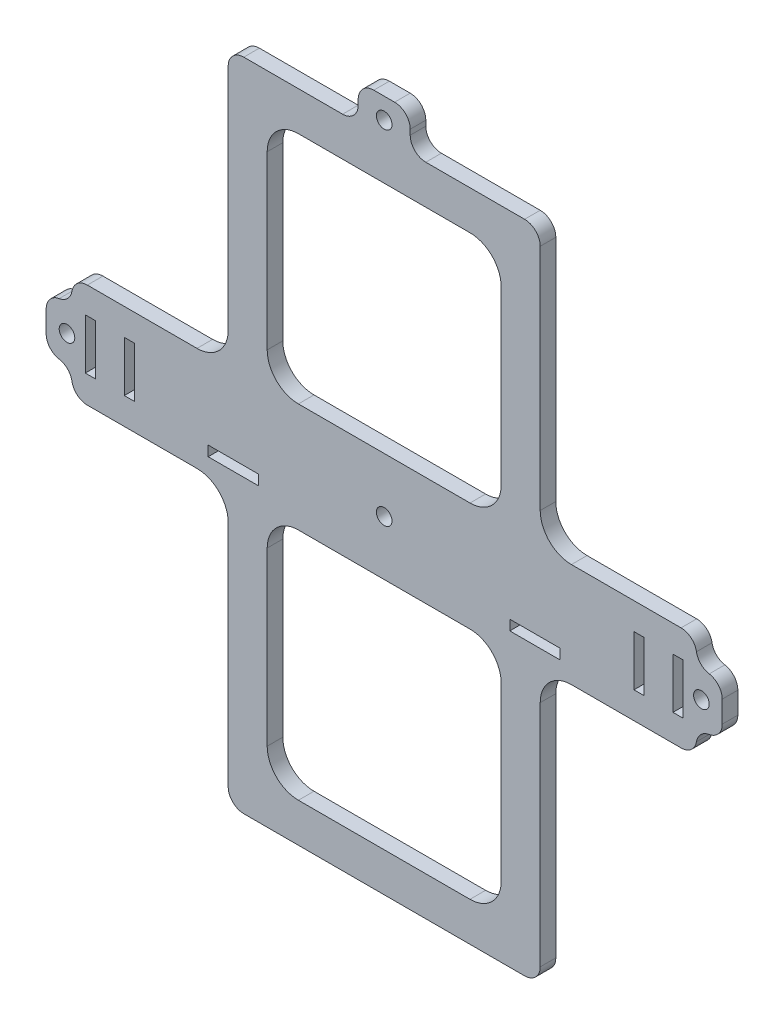
SolidWorks part; units mm, degrees
ref_plane "Спереди" through (0, 0, 0) normal (0, 0, 1) x (1, 0, 0)
ref_plane "Сверху" through (0, 0, 0) normal (0, 1, 0) x (1, 0, 0)
ref_plane "Справа" through (0, 0, 0) normal (1, 0, 0) x (0, 0, -1)
sketch "Model" plane through (0, 0, 0) normal (0, 0, 1) x (1, 0, 0)
  line L0 (-24.15, -6.975) -> (-24.15, -5.025)
  line L1 (-24.15, -5.025) -> (-33.85, -5.025)
  line L2 (-33.85, -5.025) -> (-33.85, -6.975)
  line L3 (-33.85, -6.975) -> (-24.15, -6.975)
  line L4 (33.85, -6.975) -> (33.85, -5.025)
  line L5 (33.85, -5.025) -> (24.15, -5.025)
  line L6 (24.15, -5.025) -> (24.15, -6.975)
  line L7 (24.15, -6.975) -> (33.85, -6.975)
  line L8 (49.975, 4.85) -> (48.025, 4.85)
  line L9 (48.025, 4.85) -> (48.025, -4.85)
  line L10 (48.025, -4.85) -> (49.975, -4.85)
  line L11 (49.975, -4.85) -> (49.975, 4.85)
  line L12 (-49.975, 4.85) -> (-48.025, 4.85)
  line L13 (-48.025, 4.85) -> (-48.025, -4.85)
  line L14 (-48.025, -4.85) -> (-49.975, -4.85)
  line L15 (-49.975, -4.85) -> (-49.975, 4.85)
  line L16 (-57.475, 4.85) -> (-55.525, 4.85)
  line L17 (-55.525, 4.85) -> (-55.525, -4.85)
  line L18 (-55.525, -4.85) -> (-57.475, -4.85)
  line L19 (-57.475, -4.85) -> (-57.475, 4.85)
  line L20 (57.475, 4.85) -> (55.525, 4.85)
  line L21 (55.525, 4.85) -> (55.525, -4.85)
  line L22 (55.525, -4.85) -> (57.475, -4.85)
  line L23 (57.475, -4.85) -> (57.475, 4.85)
  line L24 (36, -10) -> (57.0839, -10)
  line L25 (30, -60) -> (30, -16)
  line L26 (27, -63) -> (8, -63)
  line L27 (8, -63) -> (-27, -63)
  line L28 (-30, -60) -> (-30, -16)
  line L29 (-57.0839, -10) -> (-36, -10)
  line L30 (-65, -2.0839) -> (-65, 2.0839)
  line L31 (-36, 10) -> (-57.0839, 10)
  line L32 (-30, 16) -> (-30, 60)
  line L33 (-8, 63) -> (-27, 63)
  line L34 (-5, 66) -> (-5, 67)
  line L35 (2, 70) -> (-2, 70)
  line L36 (5, 66) -> (5, 67)
  line L37 (27, 63) -> (8, 63)
  line L38 (30, 16) -> (30, 60)
  line L39 (57.0839, 10) -> (36, 10)
  line L40 (65, -2.0839) -> (65, 2.0839)
  line L41 (-16.5, 10.5) -> (16.5, 10.5)
  line L42 (22.5, 16.5) -> (22.5, 49.5)
  line L43 (16.5, 55.5) -> (-16.5, 55.5)
  line L44 (-22.5, 49.5) -> (-22.5, 16.5)
  line L45 (-16.5, -10.5) -> (16.5, -10.5)
  line L46 (22.5, -16.5) -> (22.5, -49.5)
  line L47 (16.5, -55.5) -> (-16.5, -55.5)
  line L48 (-22.5, -49.5) -> (-22.5, -16.5)
  circle A0 centre (0, 0) radius 1.5
  circle A1 centre (0, 66) radius 1.5
  circle A2 centre (61, 0) radius 1.5
  circle A3 centre (-61, 0) radius 1.5
  arc A4 (57.0839, -10) -> (60.042, -7.5) centre (57.0839, -7) ccw
  arc A5 (27, -63) -> (30, -60) centre (27, -60) ccw
  arc A6 (-30, -60) -> (-27, -63) centre (-27, -60) ccw
  arc A7 (-60.042, -7.5) -> (-57.0839, -10) centre (-57.0839, -7) ccw
  arc A8 (-60.042, -7.5) -> (-62.5, -5.042) centre (-63, -8) ccw
  arc A9 (-65, -2.0839) -> (-62.5, -5.042) centre (-62, -2.0839) ccw
  arc A10 (-62.5, 5.042) -> (-65, 2.0839) centre (-62, 2.0839) ccw
  arc A11 (-62.5, 5.042) -> (-60.042, 7.5) centre (-63, 8) ccw
  arc A12 (-57.0839, 10) -> (-60.042, 7.5) centre (-57.0839, 7) ccw
  arc A13 (-27, 63) -> (-30, 60) centre (-27, 60) ccw
  arc A14 (-8, 63) -> (-5, 66) centre (-8, 66) ccw
  arc A15 (-2, 70) -> (-5, 67) centre (-2, 67) ccw
  arc A16 (5, 67) -> (2, 70) centre (2, 67) ccw
  arc A17 (5, 66) -> (8, 63) centre (8, 66) ccw
  arc A18 (30, 60) -> (27, 63) centre (27, 60) ccw
  arc A19 (60.042, 7.5) -> (57.0839, 10) centre (57.0839, 7) ccw
  arc A20 (60.042, 7.5) -> (62.5, 5.042) centre (63, 8) ccw
  arc A21 (65, 2.0839) -> (62.5, 5.042) centre (62, 2.0839) ccw
  arc A22 (62.5, -5.042) -> (65, -2.0839) centre (62, -2.0839) ccw
  arc A23 (62.5, -5.042) -> (60.042, -7.5) centre (63, -8) ccw
  arc A24 (-16.5, 55.5) -> (-22.5, 49.5) centre (-16.5, 49.5) ccw
  arc A25 (22.5, 49.5) -> (16.5, 55.5) centre (16.5, 49.5) ccw
  arc A26 (16.5, 10.5) -> (22.5, 16.5) centre (16.5, 16.5) ccw
  arc A27 (-22.5, 16.5) -> (-16.5, 10.5) centre (-16.5, 16.5) ccw
  arc A28 (36, -10) -> (30, -16) centre (36, -16) ccw
  arc A29 (30, 16) -> (36, 10) centre (36, 16) ccw
  arc A30 (-30, -16) -> (-36, -10) centre (-36, -16) ccw
  arc A31 (-36, 10) -> (-30, 16) centre (-36, 16) ccw
  arc A32 (-22.5, -49.5) -> (-16.5, -55.5) centre (-16.5, -49.5) ccw
  arc A33 (16.5, -55.5) -> (22.5, -49.5) centre (16.5, -49.5) ccw
  arc A34 (22.5, -16.5) -> (16.5, -10.5) centre (16.5, -16.5) ccw
  arc A35 (-16.5, -10.5) -> (-22.5, -16.5) centre (-16.5, -16.5) ccw
extrude "Бобышка-Вытянуть1" add sketch "Model" along normal blind 3
